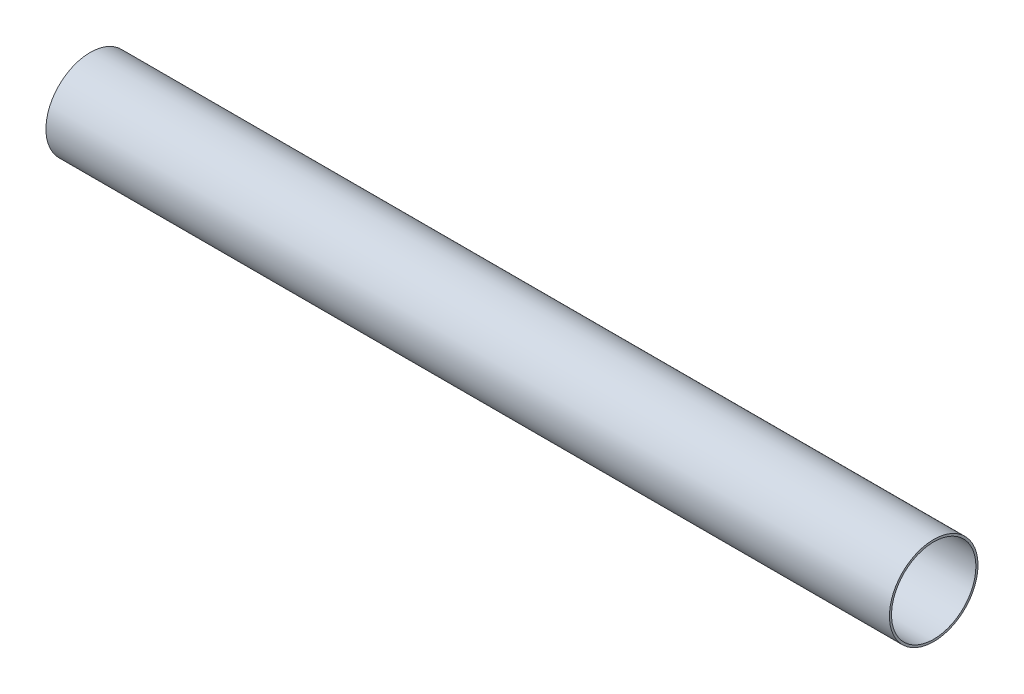
SolidWorks part; units mm, degrees
ref_plane "Front Plane" through (0, 0, 0) normal (0, 0, 1) x (1, 0, 0)
ref_plane "Top Plane" through (0, 0, 0) normal (0, 1, 0) x (1, 0, 0)
ref_plane "Right Plane" through (0, 0, 0) normal (1, 0, 0) x (0, 0, -1)
sketch "Sketch1" plane through (0, 0, 0) normal (1, 0, 0) x (0, 0, -1)
  circle A0 centre (0, 0) radius 50
  circle A1 centre (0, 0) radius 52.5
  dimension "D1" = 100
  dimension "D2" = 105
extrude "Boss-Extrude1" add sketch "Sketch1" along normal mid plane 1000
